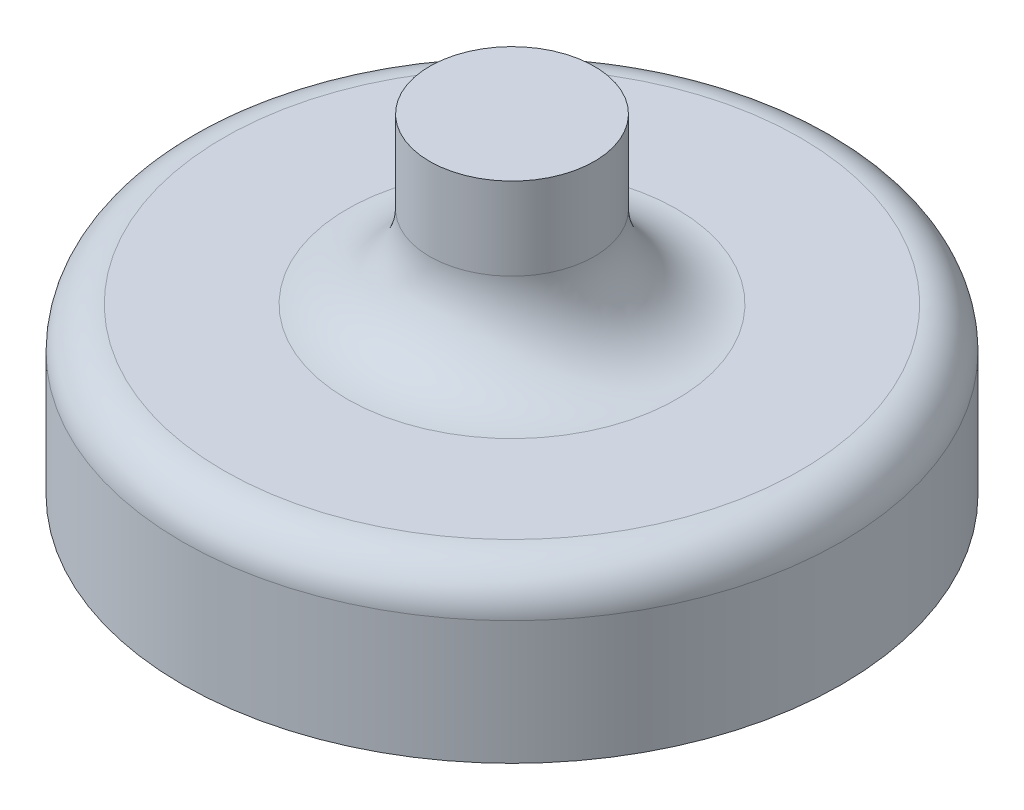
SolidWorks part; units mm, degrees
ref_plane "Front Plane" through (0, 0, 0) normal (0, 0, 1) x (1, 0, 0)
ref_plane "Top Plane" through (0, 0, 0) normal (0, 1, 0) x (1, 0, 0)
ref_plane "Right Plane" through (0, 0, 0) normal (1, 0, 0) x (0, 0, -1)
sketch "Sketch1" plane through (0, 0, 0) normal (0, 1, 0) x (1, 0, 0)
  circle A0 centre (0, 0) radius 50.8
extrude "Boss-Extrude1" add sketch "Sketch1" along normal blind 25.4
sketch "Sketch2" plane through (0, 25.4, 0) normal (0, 1, 0) x (1, 0, 0)
  circle A0 centre (0, 0) radius 12.7
extrude "Boss-Extrude2" add sketch "Sketch2" along normal blind 25.4
fillet "Fillet5" radius 12.7 1 edges at (0, 25.4, 12.7)
fillet "Fillet6" radius 6.35 1 edges at (0, 25.4, 50.8)
